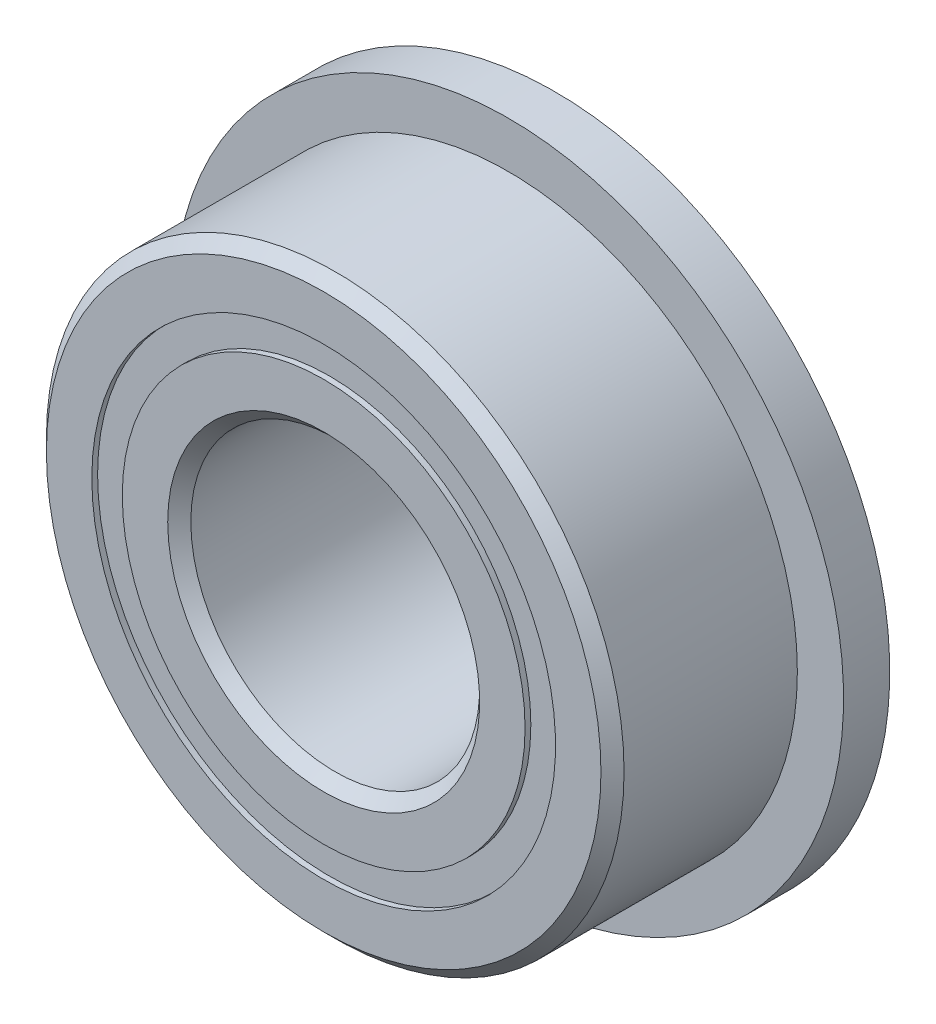
SolidWorks part; units mm, degrees
ref_plane "Front" through (0, 0, 0) normal (0, 0, 1) x (1, 0, 0)
ref_plane "Top" through (0, 0, 0) normal (0, 1, 0) x (1, 0, 0)
ref_plane "Right" through (0, 0, 0) normal (1, 0, 0) x (0, 0, -1)
sketch "Sketch1" plane through (0, 0, 0) normal (1, 0, 0) x (0, 0, -1)
  line L0 (0, 1.7997) -> (0, 0) construction
  line L1 (0, 0) -> (-4.7011, 0) construction
  line L2 (2, 5.8) -> (1.2, 5.8)
  line L3 (1.2, 5.8) -> (1.2, 5)
  line L4 (1.9, 3.75) -> (0, 3.75) construction
  line L6 (1.2, 5) -> (-1.8, 5)
  line L7 (-1.8, 5) -> (-2, 4.8)
  line L9 (-2, 4.8) -> (-2, 4.0137)
  line L11 (-2, 4.0137) -> (-1.9, 4.0137)
  line L12 (-1.9, 4.0137) -> (-1.9, 3.4863)
  line L13 (-1.9, 3.4863) -> (-2, 3.4863)
  line L14 (-2, 3.4863) -> (-2, 2.7)
  line L17 (-2, 2.7) -> (-1.8, 2.5)
  line L18 (-1.8, 2.5) -> (1.8, 2.5)
  line L20 (1.8, 2.5) -> (2, 2.7)
  line L21 (2, 2.7) -> (2, 3.4863)
  line L22 (2, 3.4863) -> (1.9, 3.4863)
  line L24 (1.9, 3.4863) -> (1.9, 4.0137)
  line L25 (1.9, 4.0137) -> (2, 4.0137)
  line L26 (2, 4.0137) -> (2, 5.8)
  line L43 (-0.8889, 4.0137) -> (-0.9272, 4.0137)
  line L44 (-0.9272, 4.0137) -> (-0.9272, 3.4863)
  line L45 (-0.9272, 3.4863) -> (-0.8889, 3.4863)
  line L46 (0.8889, 3.4863) -> (0.9272, 3.4863)
  line L47 (0.9272, 3.4863) -> (0.9272, 4.0137)
  line L48 (0.9272, 4.0137) -> (0.8889, 4.0137)
  line L63 (0, 5) -> (0, 2.5) construction
  arc A0 (0.8889, 4.0137) -> (-0.8889, 4.0137) centre (0, 3.75) ccw
  arc A1 (-0.8889, 3.4863) -> (0.8889, 3.4863) centre (0, 3.75) ccw
  dimension "D9" = 0.9272
  dimension "D1" = 5
  dimension "D2" = 10
  dimension "D3" = 4
  dimension "D4" = 0.8
  dimension "D5" = 11.6
  dimension "D6" = 45
  dimension "D7" = 0.2
  dimension "D8" = 0.1
  dimension "D10" = 0.5275
  dimension "D11" = 1.8544
revolve "Revolve1" add sketch "Sketch1" angle 360 about L1
